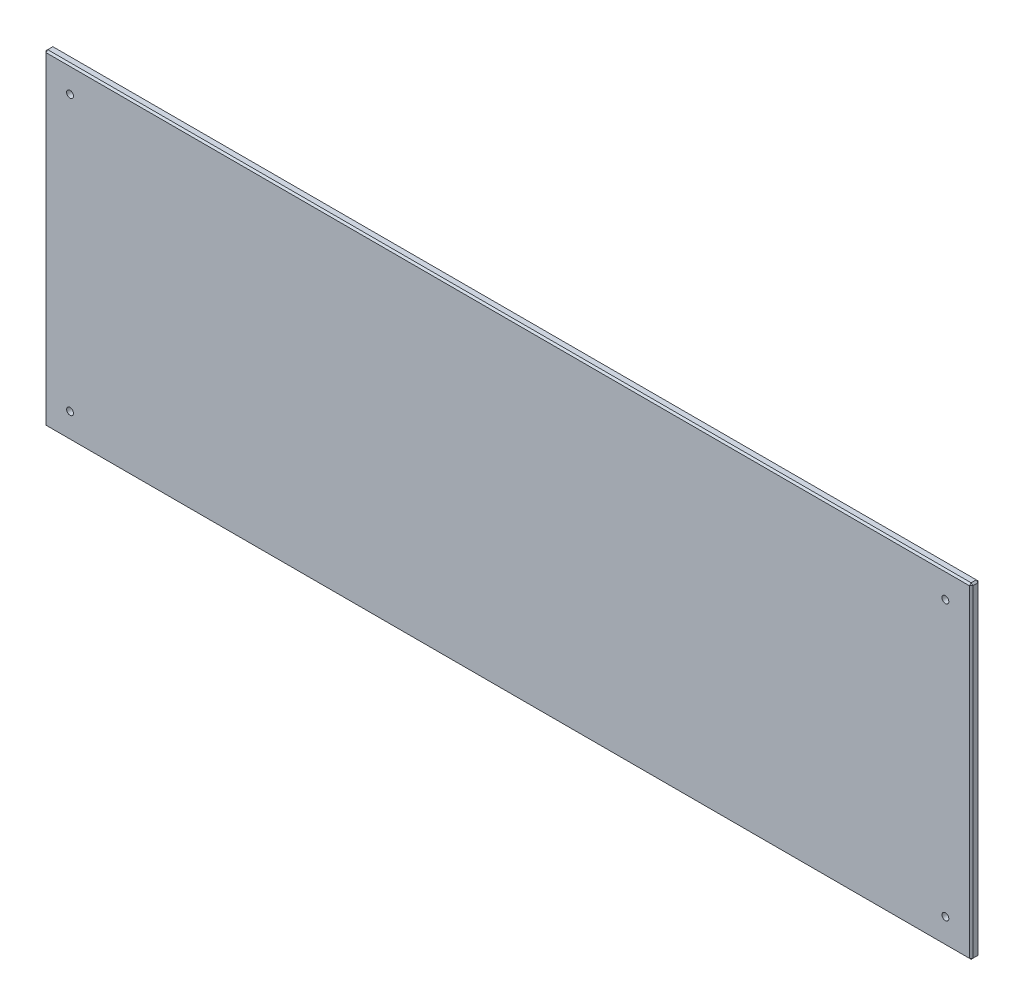
SolidWorks part; units mm, degrees
material "ABS"
ref_plane "Front Plane" through (0, 0, 0) normal (0, 0, 1) x (1, 0, 0)
ref_plane "Top Plane" through (0, 0, 0) normal (0, 1, 0) x (1, 0, 0)
ref_plane "Right Plane" through (0, 0, 0) normal (1, 0, 0) x (0, 0, -1)
sketch "Sketch1" plane through (0, 0, 0) normal (0, 0, 1) x (1, 0, 0)
  line L1 (0, 0) -> (540, 0)
  line L2 (0, 0) -> (0, 190)
  line L3 (0, 190) -> (540, 190)
  line L4 (540, 0) -> (540, 190)
  dimension "D1" = 540
  dimension "D2" = 190
extrude "Boss-Extrude1" add sketch "Sketch1" along normal blind 5
chamfer "Chamfer1" distance 1 angle 45 12 edges at (270, 0, 0) (540, 95, 0) (270, 190, 0) (0, 95, 0) (270, 190, 5) (0, 190, 2.5) (0, 95, 5) (0, 0, 2.5) (270, 0, 5) (540, 0, 2.5) (540, 95, 5) (540, 190, 2.5)
sketch "Sketch2" plane through (0, 0, 5) normal (0, 0, 1) x (1, 0, 0)
  line L0 (1, 190) -> (539, 190) construction
  line L1 (15, 175) -> (525, 175) construction
  line L2 (15, 175) -> (15, 15) construction
  line L3 (15, 15) -> (525, 15) construction
  line L4 (525, 175) -> (525, 15) construction
  line L5 (540, 189) -> (540, 1) construction
  line L6 (539, 0) -> (1, 0) construction
  line L7 (0, 1) -> (0, 189) construction
  circle A0 centre (525, 175) radius 2
  circle A1 centre (525, 15) radius 2
  circle A2 centre (15, 175) radius 2
  circle A3 centre (15, 15) radius 2
  dimension "D5" = 4
  dimension "D6" = 4
  dimension "D7" = 4
  dimension "D8" = 4
  dimension "D1" = 15
  dimension "D2" = 15
  dimension "D3" = 15
  dimension "D4" = 15
extrude "Cut-Extrude1" cut sketch "Sketch2" against normal blind 5
sketch "Sketch3" plane through (0, 0, 5) normal (0, 0, 1) x (1, 0, 0)
  line L0 (270, 189) -> (270, 1) construction
  line L1 (213, 119) -> (327, 119)
  line L2 (213, 119) -> (213, 71)
  line L3 (213, 71) -> (327, 71)
  line L4 (327, 119) -> (327, 71)
  line L5 (539, 189) -> (1, 189) construction
  line L6 (1, 1) -> (539, 1) construction
  line L7 (1, 95) -> (539, 95) construction
  line L8 (1, 189) -> (1, 1) construction
  line L9 (539, 1) -> (539, 189) construction
  dimension "D1" = 114
  dimension "D2" = 48
  dimension "D3" = 57
  dimension "D4" = 24
